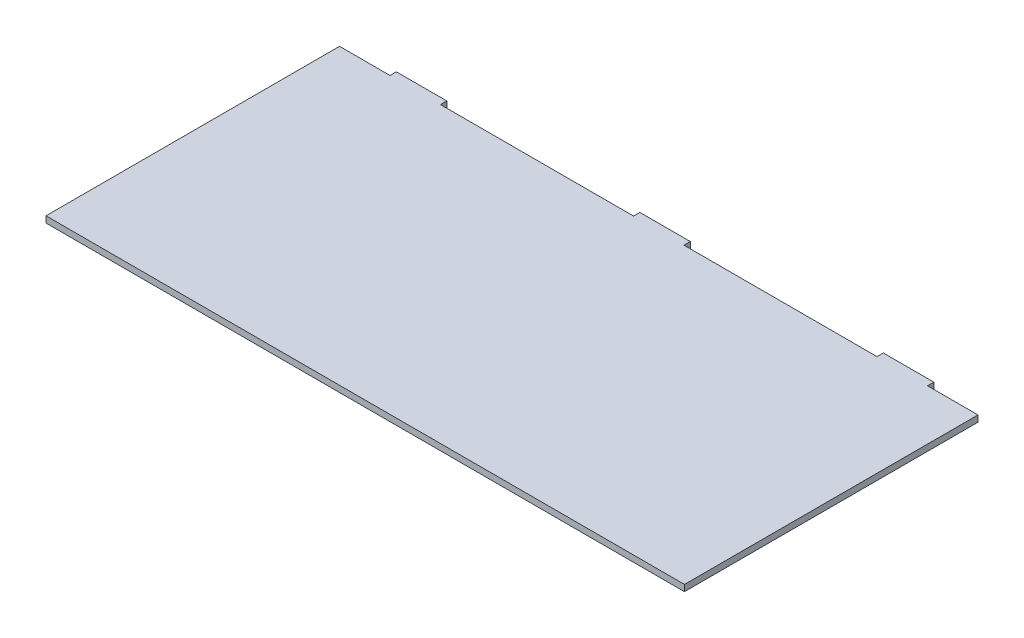
SolidWorks part; units mm, degrees
material "6061-T6 (SS)"
ref_plane "X-Y Datum" through (0, 0, 0) normal (0, 0, 1) x (1, 0, 0)
ref_plane "X-Z Datum" through (0, 0, 0) normal (0, 1, 0) x (1, 0, 0)
ref_plane "Y-Z Datum" through (0, 0, 0) normal (1, 0, 0) x (0, 0, -1)
sketch "Sketch1" plane through (0, 0, 0) normal (0, 1, 0) x (1, 0, 0)
  line L1 (0, 0) -> (321.2414, 0)
  line L2 (0, 0) -> (0, 147.6985)
  line L3 (0, 147.6985) -> (321.2414, 147.6985)
  line L4 (321.2414, 0) -> (321.2414, 147.6985)
extrude "Boss-Extrude1" add sketch "Sketch1" along normal blind 3.175
sketch "Sketch2" plane through (0, 0, -147.6985) normal (0, 0, -1) x (-1, 0, 0)
  line L0 (-321.2414, 3.175) -> (0, 3.175) construction
  line L1 (-321.2414, 3.175) -> (-321.2414, 0) construction
  line L2 (-321.2414, 0) -> (0, 0) construction
  line L3 (0, 3.175) -> (0, 0) construction
  line L4 (-295.8414, 3.175) -> (-270.4414, 3.175)
  line L5 (-295.8414, 3.175) -> (-295.8414, 0)
  line L6 (-295.8414, 0) -> (-270.4414, 0)
  line L7 (-270.4414, 3.175) -> (-270.4414, 0)
  line L8 (-173.3207, 3.175) -> (-147.9207, 3.175)
  line L9 (-173.3207, 3.175) -> (-173.3207, 0)
  line L10 (-173.3207, 0) -> (-147.9207, 0)
  line L11 (-147.9207, 3.175) -> (-147.9207, 0)
  line L12 (-50.8, 3.175) -> (-25.4, 3.175)
  line L13 (-50.8, 3.175) -> (-50.8, 0)
  line L14 (-50.8, 0) -> (-25.4, 0)
  line L15 (-25.4, 3.175) -> (-25.4, 0)
extrude "Boss-Extrude2" add sketch "Sketch2" along normal blind 3.175
